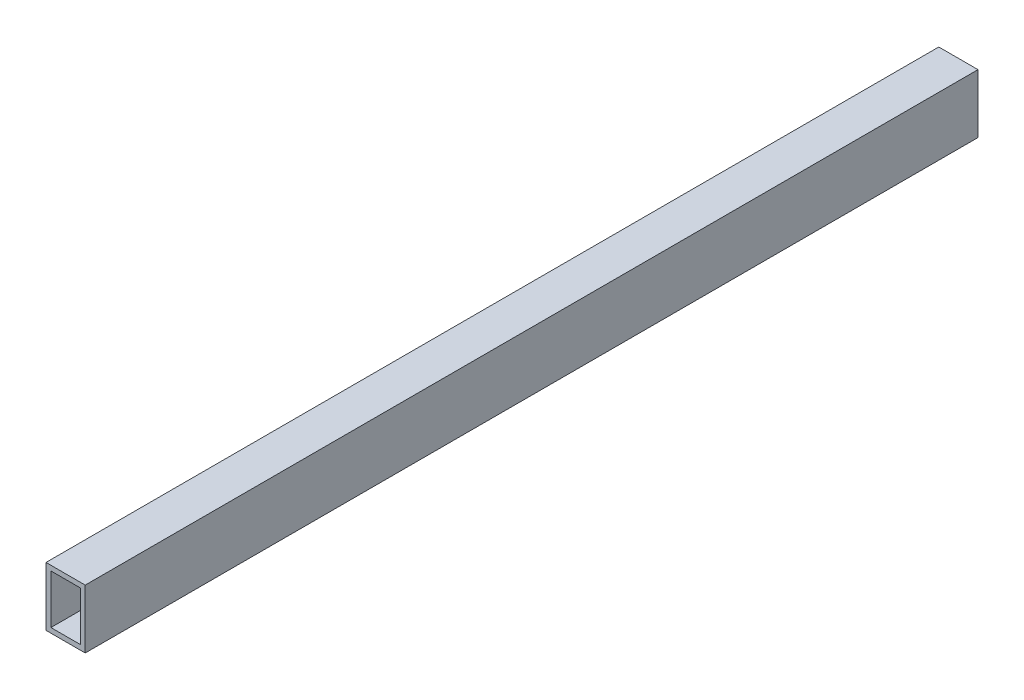
SolidWorks part; units mm, degrees
ref_plane "Front Plane" through (0, 0, 0) normal (0, 0, 1) x (1, 0, 0)
ref_plane "Top Plane" through (0, 0, 0) normal (0, 1, 0) x (1, 0, 0)
ref_plane "Right Plane" through (0, 0, 0) normal (1, 0, 0) x (0, 0, -1)
sketch "Sketch2" plane through (0, 0, 0) normal (0, 0, 1) x (1, 0, 0)
  line L1 (-12.7, 19.05) -> (12.7, 19.05)
  line L2 (-12.7, 19.05) -> (-12.7, -19.05)
  line L3 (-12.7, -19.05) -> (12.7, -19.05)
  line L4 (12.7, 19.05) -> (12.7, -19.05)
  line L5 (-12.7, 19.05) -> (12.7, -19.05) construction
  line L6 (-12.7, -19.05) -> (12.7, 19.05) construction
  line L7 (-9.525, 15.875) -> (9.525, 15.875)
  line L8 (-9.525, 15.875) -> (-9.525, -15.875)
  line L9 (-9.525, -15.875) -> (9.525, -15.875)
  line L10 (9.525, 15.875) -> (9.525, -15.875)
  line L11 (-9.525, 15.875) -> (9.525, -15.875) construction
  line L12 (-9.525, -15.875) -> (9.525, 15.875) construction
  point P0 (0, 0)
  point P6 (0, 0)
  dimension "D1" = 25.4
  dimension "D2" = 38.1
  dimension "D3" = 19.05
  dimension "D4" = 31.75
extrude "Boss-Extrude1" add sketch "Sketch2" along normal blind 578.104
